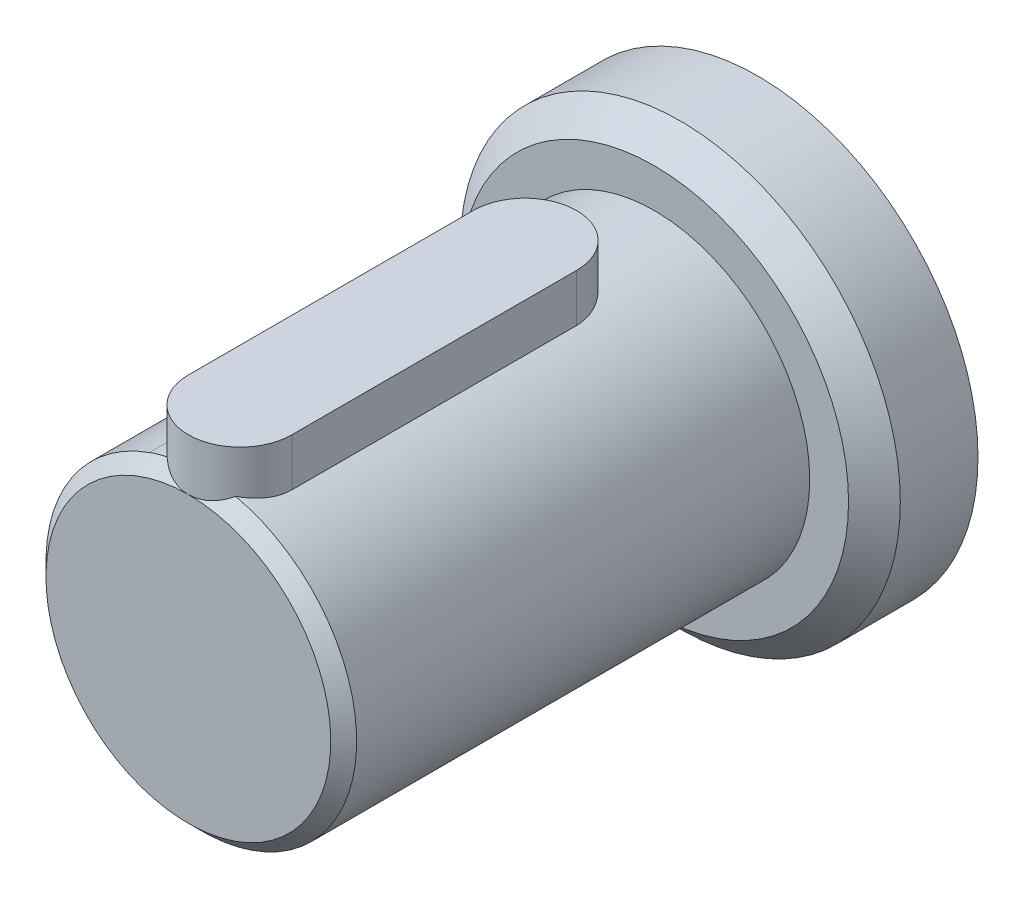
SolidWorks part; units mm, degrees
ref_plane "Plan de face" through (0, 0, 0) normal (0, 0, 1) x (1, 0, 0)
ref_plane "Plan de dessus" through (0, 0, 0) normal (0, 1, 0) x (1, 0, 0)
ref_plane "Plan de droite" through (0, 0, 0) normal (1, 0, 0) x (0, 0, -1)
sketch "Esquisse1" plane through (0, 0, 0) normal (0, 0, 1) x (1, 0, 0)
  circle A0 centre (0, 0) radius 8.5
  dimension "D1" = 17
extrude "Boss.-Extru.1" add sketch "Esquisse1" along normal blind 4
sketch "Esquisse2" plane through (0, 0, 4) normal (0, 0, 1) x (1, 0, 0)
  circle A0 centre (0, 0) radius 6
  dimension "D1" = 12
extrude "Boss.-Extru.2" add sketch "Esquisse2" along normal blind 18
chamfer "Chanfrein1" distance 1 angle 45 1 edges at (8.5, 0, 4)
chamfer "Chanfrein2" distance 0.5 angle 45 1 edges at (6, 0, 22)
ref_plane "Plan1" through (0, 6, 0) normal (0, 1, 0) x (1, 0, 0)
sketch "Esquisse3" plane through (0, 6, 0) normal (0, 1, 0) x (1, 0, 0)
  line L0 (0, -30.6066) -> (0, 7.4045) construction
  line L1 (0, -20) -> (0, -9) construction
  line L2 (-2, -20) -> (-2, -9)
  line L3 (2, -20) -> (2, -9)
  line L4 (-5.5, -22) -> (5.5, -22) construction
  line L5 (-9.0695, -7) -> (12.7701, -7) construction
  line L6 (-9.912, -22) -> (11.8854, -22) construction
  arc A0 (-2, -20) -> (2, -20) centre (0, -20) ccw
  arc A1 (2, -9) -> (-2, -9) centre (0, -9) ccw
  point P5 (0, -14.5)
  dimension "D1" = 4
  dimension "D2" = 15
extrude "Boss.-Extru.3" add sketch "Esquisse3" along normal blind 1.5 and the other way blind 1
